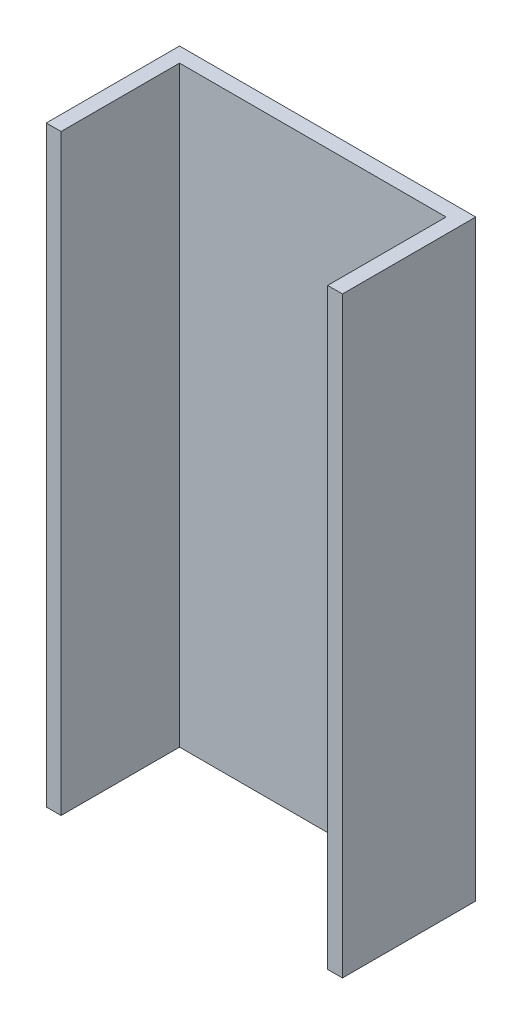
SolidWorks part; units mm, degrees
ref_plane "前视基准面" through (0, 0, 0) normal (0, 0, 1) x (1, 0, 0)
ref_plane "上视基准面" through (0, 0, 0) normal (0, 1, 0) x (1, 0, 0)
ref_plane "右视基准面" through (0, 0, 0) normal (1, 0, 0) x (0, 0, -1)
other "Configuration Table"
sketch "草图1" plane through (0, 0, 0) normal (0, 1, 0) x (1, 0, 0)
  line L0 (-1000, -400) -> (-1000, 500)
  line L1 (-1000, 500) -> (1000, 500)
  line L2 (1000, 500) -> (1000, -400)
  line L3 (1000, -400) -> (900, -400)
  line L4 (900, -400) -> (900, 400)
  line L5 (900, 400) -> (-900, 400)
  line L6 (-900, 400) -> (-900, -400)
  line L7 (-1000, -400) -> (-900, -400)
  line L8 (0, 0) -> (0, -574.0596) construction
  dimension "D1" = 2000
  dimension "D2" = 1800
  dimension "D3" = 900
  dimension "D4" = 100
  dimension "D6" = 100
  dimension "D7" = 400
extrude "凸台-拉伸1" add sketch "草图1" along normal blind 4000
